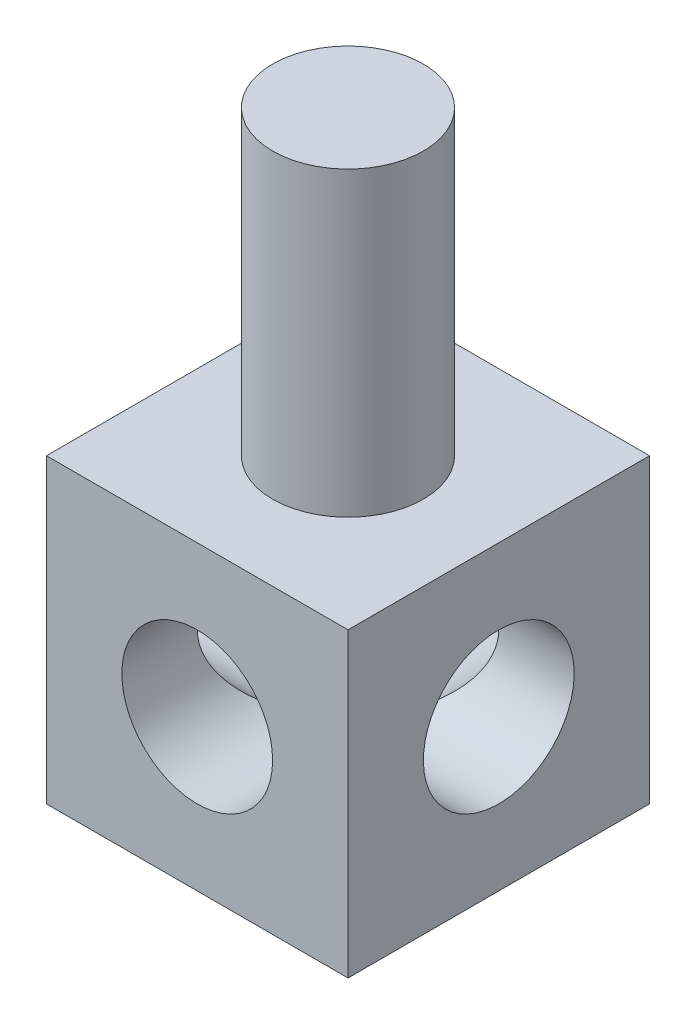
SolidWorks part; units mm, degrees
ref_plane "Front Plane" through (0, 0, 0) normal (0, 0, 1) x (1, 0, 0)
ref_plane "Top Plane" through (0, 0, 0) normal (0, 1, 0) x (1, 0, 0)
ref_plane "Right Plane" through (0, 0, 0) normal (1, 0, 0) x (0, 0, -1)
sketch "Sketch1" plane through (0, 0, 0) normal (0, 0, 1) x (1, 0, 0)
  line L1 (0, 0) -> (10, 0)
  line L2 (0, 0) -> (0, 10)
  line L3 (0, 10) -> (10, 10)
  line L4 (10, 0) -> (10, 10)
  dimension "D1" = 10
  dimension "D2" = 10
extrude "Boss-Extrude1" add sketch "Sketch1" along normal blind 10
sketch "Sketch2" plane through (0, 10, 0) normal (0, 1, 0) x (1, 0, 0)
  line L0 (0, -10) -> (0, 0) construction
  line L1 (10, 0) -> (0, 0) construction
  circle A0 centre (5, -5) radius 2.5
  dimension "D1" = 5
  dimension "D2" = 5
  dimension "D3" = 5
extrude "Boss-Extrude2" add sketch "Sketch2" along normal blind 10
sketch "Sketch3" plane through (0, 0, 10) normal (0, 0, 1) x (1, 0, 0)
  line L0 (0, 10) -> (0, 0) construction
  line L2 (0, 0) -> (10, 0) construction
  circle A0 centre (5, 5) radius 2.5
  dimension "D1" = 5
  dimension "D2" = 5
  dimension "D3" = 5
extrude "Cut-Extrude1" cut sketch "Sketch3" against normal blind 10 contours A0
sketch "Sketch4" plane through (10, 0, 0) normal (1, 0, 0) x (0, 0, -1)
  line L0 (-10, 0) -> (-10, 10) construction
  line L1 (-10, 10) -> (0, 10) construction
  circle A0 centre (-5, 5) radius 2.5
  dimension "D1" = 5
  dimension "D2" = 5
  dimension "D3" = 5
extrude "Cut-Extrude2" cut sketch "Sketch4" against normal blind 10
